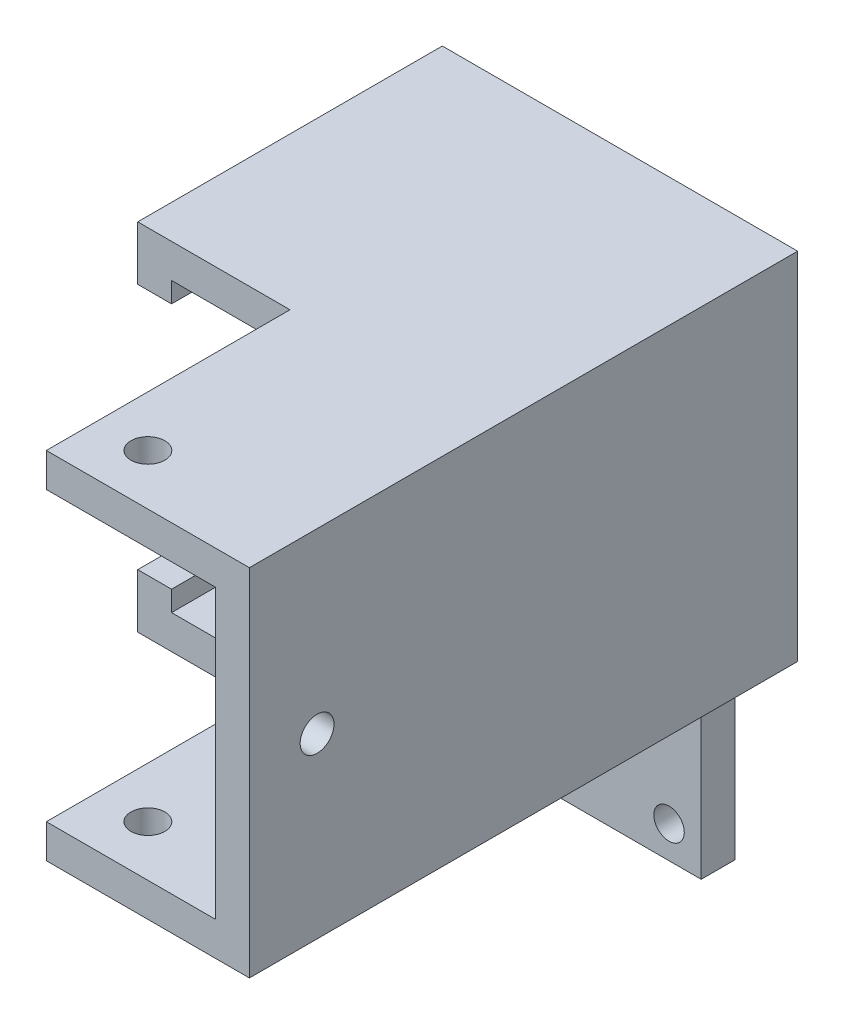
SolidWorks part; units mm, degrees
ref_plane "Front Plane" through (0, 0, 0) normal (0, 0, 1) x (1, 0, 0)
ref_plane "Top Plane" through (0, 0, 0) normal (0, 1, 0) x (1, 0, 0)
ref_plane "Right Plane" through (0, 0, 0) normal (1, 0, 0) x (0, 0, -1)
sketch "Sketch1" plane through (0, 0, 0) normal (0, 0, 1) x (1, 0, 0)
  line L0 (0, 30) -> (-9.25, 30)
  line L1 (0, 0) -> (34, 0)
  line L2 (0, 0) -> (0, 30)
  line L4 (34, 0) -> (34, 30)
  line L5 (-9.25, 30) -> (-9.25, 82.5)
  line L6 (-9.25, 82.5) -> (43.25, 82.5)
  line L7 (43.25, 82.5) -> (43.25, 30)
  line L8 (34, 30) -> (43.25, 30)
  circle A0 centre (4.75, 25.25) radius 2.25
  circle A1 centre (29.25, 25.25) radius 2.25
  circle A2 centre (29.25, 4.75) radius 2.25
  circle A3 centre (4.75, 4.75) radius 2.25
  dimension "D3" = 4.5
  dimension "D6" = 4.5
  dimension "D13" = 4.5
  dimension "D14" = 4.5
  dimension "D15" = 52.5
  dimension "D16" = 9.25
  dimension "D1" = 30
  dimension "D2" = 34
  dimension "D4" = 4.75
  dimension "D8" = 4.75
  dimension "D9" = 4.75
  dimension "D10" = 4.75
  dimension "D11" = 4.75
  dimension "D12" = 4.75
  dimension "D17" = 52.5
extrude "Boss-Extrude1" add sketch "Sketch1" along normal blind 5
sketch "Sketch2" plane through (0, 0, 5) normal (0, 0, 1) x (1, 0, 0)
  line L1 (-9.25, 82.5) -> (43.25, 82.5)
  line L2 (-9.25, 82.5) -> (-9.25, 30)
  line L3 (-9.25, 30) -> (43.25, 30)
  line L4 (43.25, 82.5) -> (43.25, 30)
  line L5 (-4.25, 77.5) -> (38.25, 77.5)
  line L6 (-4.25, 77.5) -> (-4.25, 35)
  line L7 (-4.25, 35) -> (38.25, 35)
  line L8 (38.25, 77.5) -> (38.25, 35)
  dimension "D1" = 5
  dimension "D2" = 5
  dimension "D3" = 5
  dimension "D4" = 5
extrude "Boss-Extrude2" add sketch "Sketch2" along normal blind 40
sketch "Sketch5" plane through (0, 0, 45) normal (0, 0, 1) x (1, 0, 0)
  line L0 (-9.25, 30) -> (43.25, 30) construction
  line L6 (43.25, 82.5) -> (-9.25, 82.5) construction
  line L7 (43.25, 82.5) -> (43.25, 30)
  line L8 (13.25, 82.5) -> (13.25, 77.5)
  line L9 (38.25, 77.5) -> (-4.25, 77.5) construction
  line L10 (13.25, 77.5) -> (38.25, 77.5)
  line L12 (0, 30) -> (34, 30) construction
  line L13 (13.25, 30) -> (13.25, 35)
  line L14 (-4.25, 35) -> (38.25, 35) construction
  line L15 (13.25, 35) -> (38.25, 35)
  line L16 (13.25, 82.5) -> (43.25, 82.5)
  line L17 (43.25, 30) -> (13.25, 30)
  line L18 (38.25, 77.5) -> (38.25, 35)
  dimension "D1" = 25
  dimension "D2" = 0
  dimension "D3" = 5
extrude "Boss-Extrude3" add sketch "Sketch5" along normal blind 36
sketch "Sketch6" plane through (0, 77.5, 0) normal (0, -1, 0) x (1, 0, 0)
  line L0 (13.25, 81) -> (13.25, 45) construction
  line L1 (13.25, 81) -> (38.25, 81) construction
  circle A0 centre (20.75, 73.5) radius 2.5
  dimension "D1" = 5
  dimension "D2" = 7.5
  dimension "D3" = 7.5
extrude "Cut-Extrude2" cut sketch "Sketch6" against normal through all both and the other way through all
sketch "Sketch7" plane through (43.25, 0, 0) normal (1, 0, 0) x (0, 0, -1)
  line L0 (-81, 30) -> (-81, 82.5) construction
  line L2 (-81, 82.5) -> (0, 82.5) construction
  circle A0 centre (-71, 56.25) radius 2.5
  dimension "D1" = 5
  dimension "D2" = 10
  dimension "D3" = 26.25
extrude "Cut-Extrude3" cut sketch "Sketch7" against normal through all both
sketch "Sketch8" plane through (-9.25, 0, 0) normal (-1, 0, 0) x (0, 0, 1)
  line L0 (45, 82.5) -> (45, 30) construction
  line L1 (45, 74.5) -> (5, 74.5)
  line L2 (45, 74.5) -> (45, 38)
  line L3 (45, 38) -> (5, 38)
  line L4 (5, 74.5) -> (5, 38)
  line L5 (45, 82.5) -> (0, 82.5) construction
  line L6 (45, 30) -> (0, 30) construction
  line L7 (0, 82.5) -> (0, 30) construction
  point P8 (22.5, 82.5)
  dimension "D1" = 8
  dimension "D2" = 8
  dimension "D3" = 5
extrude "Cut-Extrude4" cut sketch "Sketch8" against normal blind 24
